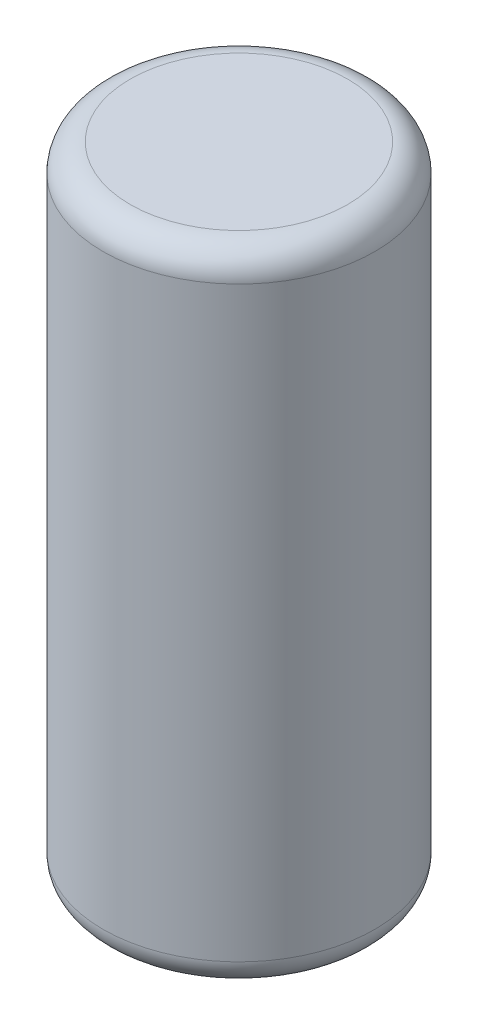
SolidWorks part; units mm, degrees
ref_plane "前基準面" through (0, 0, 0) normal (0, 0, 1) x (1, 0, 0)
ref_plane "上基準面" through (0, 0, 0) normal (0, 1, 0) x (1, 0, 0)
ref_plane "右基準面" through (0, 0, 0) normal (1, 0, 0) x (0, 0, -1)
ref_plane "平面1" through (0, 0, 0) normal (0, 0, -1) x (-1, 0, 0)
sketch "草圖1" plane through (0, 0, 0) normal (0, 0, -1) x (-1, 0, 0)
  line L0 (-2, 0) -> (0, 0)
  line L1 (0, 0) -> (0, 11.8)
  line L2 (0, 11.8) -> (-2, 11.8)
  line L3 (-2.5, 11.3) -> (-2.5, 0.5)
  line L4 (0, -0.0022) -> (0, 11.8022) construction
  arc A0 (-2, 11.8) -> (-2.5, 11.3) centre (-2, 11.3) ccw
  arc A1 (-2.5, 0.5) -> (-2, 0) centre (-2, 0.5) ccw
revolve "旋轉1" add sketch "草圖1" angle 360 about L4
